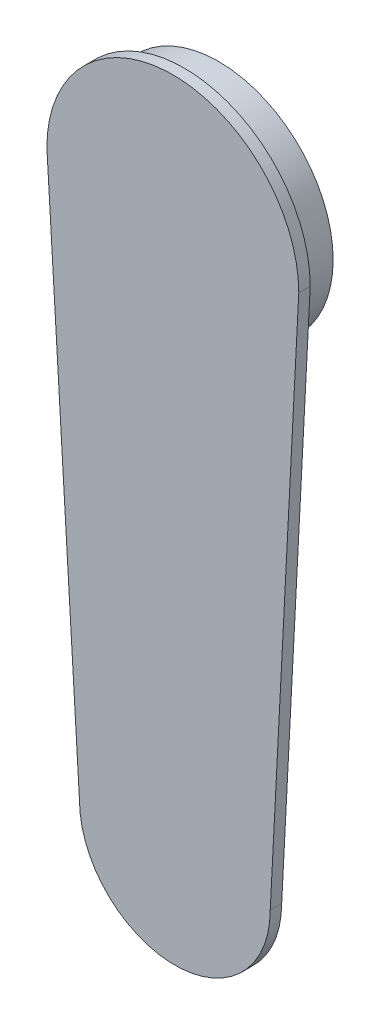
SolidWorks part; units mm, degrees
ref_plane "Front Plane" through (0, 0, 0) normal (0, 0, 1) x (1, 0, 0)
ref_plane "Top Plane" through (0, 0, 0) normal (0, 1, 0) x (1, 0, 0)
ref_plane "Right Plane" through (0, 0, 0) normal (1, 0, 0) x (0, 0, -1)
sketch "Sketch1" plane through (0, 0, 0) normal (0, 0, 1) x (1, 0, 0)
  line L1 (-55, 0) -> (-40.7681, -239.6759)
  line L2 (42.5319, -239.6759) -> (55, 0)
  circle A0 centre (0, 0) radius 55
  circle A1 centre (0.8819, -239.6759) radius 41.65
extrude "Boss-Extrude1" add sketch "Sketch1" along normal blind 5 and the other way blind 0.0001 contours L2 A0 L1 | A1 L2 A0 L1 | A1 L2
sketch "Sketch2" plane through (0, 0, -0.0001) normal (0, 0, -1) x (-1, 0, 0)
  circle A0 centre (0, 0) radius 50
extrude "Boss-Extrude2" add sketch "Sketch2" along normal blind 15
